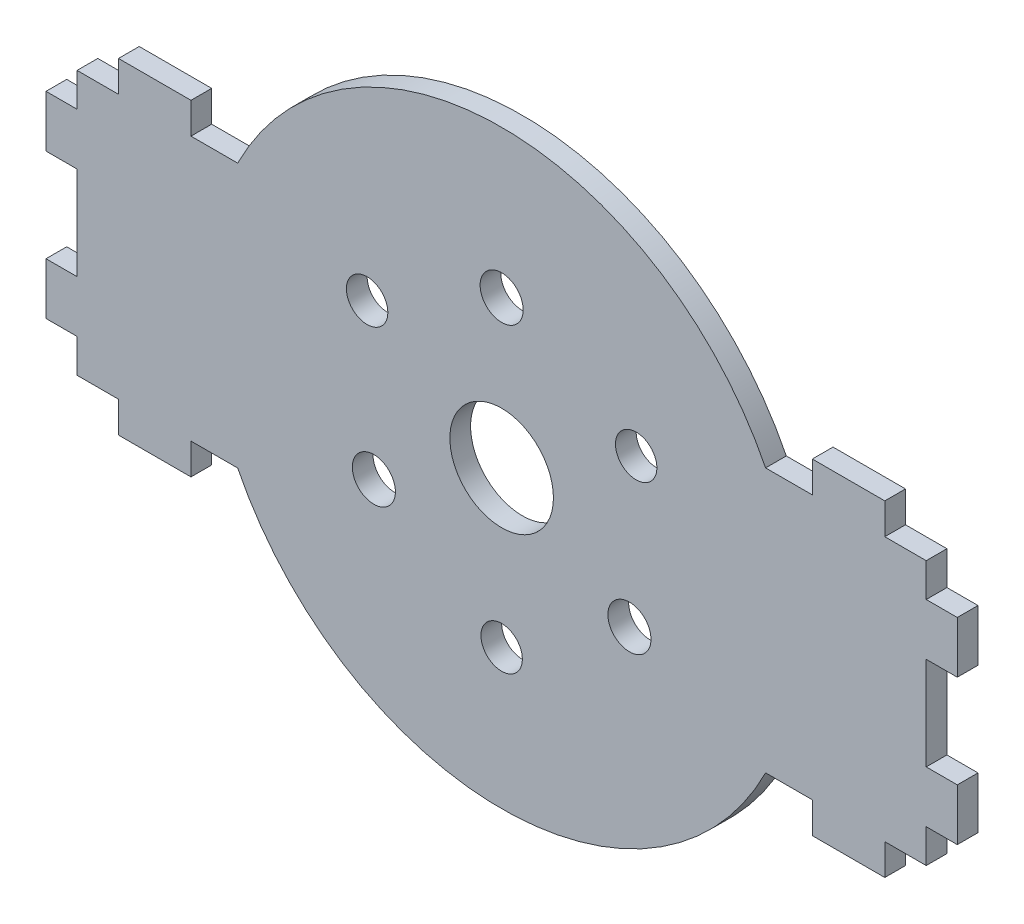
SolidWorks part; units mm, degrees
ref_plane "前视基准面" through (0, 0, 0) normal (0, 0, 1) x (1, 0, 0)
ref_plane "上视基准面" through (0, 0, 0) normal (0, 1, 0) x (1, 0, 0)
ref_plane "右视基准面" through (0, 0, 0) normal (1, 0, 0) x (0, 0, -1)
sketch "草图1" plane through (0, 0, 0) normal (0, 0, 1) x (1, 0, 0)
  line L19 (-37, -12.75) -> (-41, -12.75)
  line L143 (-41, 1.5) -> (-41, -1.5)
  line L145 (-37, -15.75) -> (-37, -12.75)
  line L152 (-30, -12.75) -> (-30, -15.75)
  line L205 (-30, 12.75) -> (-25.489, 12.75)
  line L238 (-30, -12.75) -> (-25.489, -12.75)
  line L269 (25.489, -12.75) -> (30, -12.75)
  line L270 (25.489, 12.75) -> (30, 12.75)
  line L271 (-37, -15.75) -> (-30, -15.75)
  line L275 (37, -15.75) -> (30, -15.75)
  line L286 (30, -12.75) -> (30, -15.75)
  line L287 (37, -15.75) -> (37, -12.75)
  line L288 (37, -12.75) -> (41, -12.75)
  line L291 (37, 12.75) -> (41, 12.75)
  line L292 (37, 15.75) -> (37, 12.75)
  line L293 (30, 12.75) -> (30, 15.75)
  line L304 (37, 15.75) -> (30, 15.75)
  line L310 (-37, 15.75) -> (-30, 15.75)
  line L325 (-30, 12.75) -> (-30, 15.75)
  line L326 (-37, 15.75) -> (-37, 12.75)
  line L327 (-37, 12.75) -> (-41, 12.75)
  line L337 (-41, 1.5) -> (-41, 4.5)
  line L338 (-41, 4.5) -> (-44, 4.5)
  line L339 (-44, 4.5) -> (-44, 9.5)
  line L340 (-44, 9.5) -> (-41, 9.5)
  line L341 (-41, 9.5) -> (-41, 12.75)
  line L342 (-41, -9.5) -> (-41, -12.75)
  line L343 (-44, -9.5) -> (-41, -9.5)
  line L344 (-44, -4.5) -> (-44, -9.5)
  line L345 (-41, -4.5) -> (-44, -4.5)
  line L346 (-41, -1.5) -> (-41, -4.5)
  line L358 (41, -1.5) -> (41, -4.5)
  line L359 (41, -4.5) -> (44, -4.5)
  line L360 (44, -4.5) -> (44, -9.5)
  line L361 (44, -9.5) -> (41, -9.5)
  line L362 (41, -9.5) -> (41, -12.75)
  line L363 (41, 9.5) -> (41, 12.75)
  line L364 (44, 9.5) -> (41, 9.5)
  line L365 (44, 4.5) -> (44, 9.5)
  line L366 (41, 4.5) -> (44, 4.5)
  line L367 (41, 1.5) -> (41, 4.5)
  line L369 (41, 1.5) -> (41, -1.5)
  line L370 (0, 0) -> (0, 14.25) construction
  line L371 (0, 0) -> (-17.8104, 10.2828) construction
  arc A11 (-25.489, -12.75) -> (25.489, -12.75) centre (0, 0) ccw
  arc A12 (-25.489, 12.75) -> (25.489, 12.75) centre (0, 0) cw
  circle A13 centre (0, 0) radius 15 construction
  circle A14 centre (0, 0) radius 14.25 construction
  circle A21 centre (0, 14.25) radius 2.08
  circle A22 centre (12.3409, -7.125) radius 2.08
  circle A23 centre (-12.3409, -7.125) radius 2.08
  circle A24 centre (0, 0) radius 5
  circle A26 centre (-12.9904, 7.5) radius 2
  circle A27 centre (12.9904, 7.5) radius 2
  circle A28 centre (0, -15) radius 2
  dimension "D1" = 60
  dimension "D3" = 3
  dimension "D2" = 3
extrude "凸台-拉伸2" add sketch "草图1" along normal blind 2
